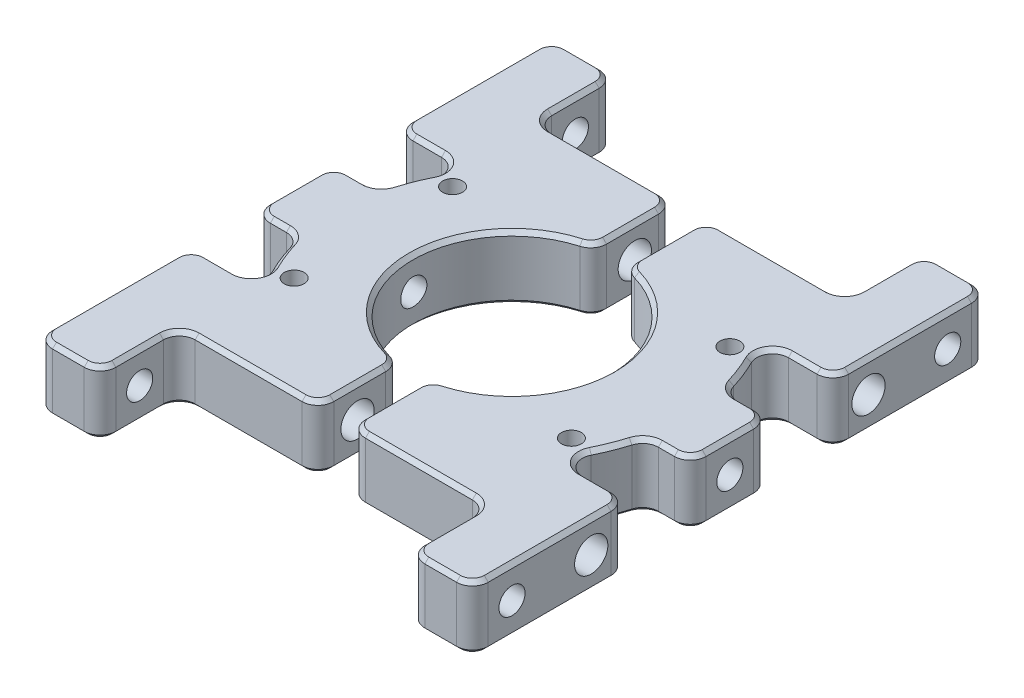
SolidWorks part; units mm, degrees
material "6061 合金"
ref_plane "前视基准面" through (0, 0, 0) normal (0, 0, 1) x (1, 0, 0)
ref_plane "上视基准面" through (0, 0, 0) normal (0, 1, 0) x (1, 0, 0)
ref_plane "右视基准面" through (0, 0, 0) normal (1, 0, 0) x (0, 0, -1)
sketch "草图1" plane through (0, 0, 0) normal (0, 1, 0) x (1, 0, 0)
  line L1 (-27.5, 22.5) -> (-2, 22.5)
  line L2 (-27.5, 22.5) -> (-27.5, -22.5)
  line L3 (-27.5, -22.5) -> (-2, -22.5)
  line L4 (27.5, 22.5) -> (27.5, -22.5)
  line L5 (-27.5, 22.5) -> (27.5, -22.5) construction
  line L6 (-27.5, -22.5) -> (27.5, 22.5) construction
  line L8 (-2, 22.5) -> (-2, 12.339)
  line L10 (2, 22.5) -> (2, 12.339)
  line L11 (2, 22.5) -> (27.5, 22.5)
  line L13 (2, -22.5) -> (27.5, -22.5)
  line L16 (2, -12.339) -> (2, -22.5)
  line L17 (-2, -12.339) -> (-2, -22.5)
  arc A0 (-2, 12.339) -> (-2, -12.339) centre (0, 0) ccw
  arc A1 (2, -12.339) -> (2, 12.339) centre (0, 0) ccw
  point P7 (0, 25)
  point P12 (0, 0)
  dimension "D1" = 25
  dimension "D2" = 55
  dimension "D3" = 45
  dimension "D4" = 4
  dimension "D5" = 2
  dimension "D6" = 4
  dimension "D7" = 2
extrude "凸台-拉伸1" add sketch "草图1" along normal mid plane 8 contours A0 L8 L1 L2 L3 | A0 L10 L3 L4 L1
sketch "草图7" plane through (0, 4, 0) normal (0, 1, 0) x (1, 0, 0)
  line L0 (27.5, 22.5) -> (27.5, -22.5) construction
  line L1 (19.5, 32.5) -> (27.5, 32.5)
  line L2 (19.5, 32.5) -> (19.5, -32.5)
  line L3 (19.5, -32.5) -> (27.5, -32.5)
  line L4 (27.5, 32.5) -> (27.5, -32.5)
  line L5 (-27.5, 32.5) -> (-19.5, 32.5)
  line L6 (-27.5, 32.5) -> (-27.5, -32.5)
  line L7 (-27.5, -32.5) -> (-19.5, -32.5)
  line L8 (-19.5, 32.5) -> (-19.5, -32.5)
  line L9 (-27.5, 22.5) -> (-27.5, -22.5) construction
  dimension "D1" = 8
  dimension "D2" = 65
  dimension "D3" = 32.5
extrude "凸台-拉伸2" add sketch "草图7" against normal up to surface (8 mm away) up to face at (12.25, -4, 0)
sketch "草图8" plane through (27.5, 0, 0) normal (1, 0, 0) x (0, 0, -1)
  line L0 (-17.5, 0) -> (17.5, 0) construction
  circle A0 centre (-17.5, 0) radius 2.1
  circle A1 centre (17.5, 0) radius 2.1
  circle A2 centre (0, 0) radius 1.5
  point P3 (0, 0)
  dimension "D2" = 4.2
  dimension "D3" = 3
  dimension "D1" = 35
extrude "切除-拉伸2" cut sketch "草图8" against normal through all
sketch "草图11" plane through (27.5, 0, 0) normal (1, 0, 0) x (0, 0, -1)
  line L0 (-27.5, 0) -> (27.5, 0) construction
  line L1 (32.5, -4) -> (32.5, 4) construction
  line L2 (-32.5, -4) -> (-32.5, 4) construction
  circle A0 centre (-27.5, 0) radius 1.5
  circle A1 centre (27.5, 0) radius 1.5
  dimension "D3" = 3
  dimension "D1" = 5
  dimension "D2" = 5
extrude "切除-拉伸3" cut sketch "草图11" against normal through all
sketch "草图12" plane through (0, 4, 0) normal (0, 1, 0) x (1, 0, 0)
  line L0 (-27.5, 0) -> (27.5, 0) construction
  line L1 (-27.5, 32.5) -> (-27.5, -32.5) construction
  line L2 (27.5, 32.5) -> (27.5, -32.5) construction
  line L3 (-27.5, -5) -> (27.5, -5)
  line L4 (-27.5, 5) -> (27.5, 5)
  line L5 (-27.5, -13) -> (27.5, -13)
  line L6 (-27.5, 13) -> (27.5, 13)
  line L7 (27.5, -13) -> (27.5, 13)
  line L8 (-27.5, 13) -> (-27.5, -13)
  line L10 (-17.5, 10) -> (17.5, 10) construction
  line L11 (-17.5, 10) -> (-17.5, -10) construction
  line L12 (-17.5, -10) -> (17.5, -10) construction
  line L13 (17.5, 10) -> (17.5, -10) construction
  line L14 (-17.5, 10) -> (17.5, -10) construction
  line L15 (-17.5, -10) -> (17.5, 10) construction
  circle A0 centre (0, 0) radius 22.5
  circle A1 centre (-17.5, -10) radius 1
  circle A2 centre (-17.5, 10) radius 1
  circle A3 centre (17.5, 10) radius 1
  circle A4 centre (17.5, -10) radius 1
  point P26 (19.8831, -10)
  line M6 (-27.5, 32.5) -> (-27.5, -32.5)
  dimension "D1" = 45
  dimension "D8" = 2
  dimension "D6" = 20
  dimension "D7" = 35
  dimension "D2" = 5
  dimension "D3" = 5
  dimension "D4" = 13
  dimension "D5" = 13
extrude "切除-拉伸5" cut sketch "草图12" against normal through all contours A0 L6 L4 M6 | A0 L3 L5 M6 | A0 L5 L7 L3 | A0 L4 L7 L6 | A2 | A1 | A4 | A3
fillet "圆角1" radius 2 18 edges at (27.5, 0, 5) (27.5, 0, -5) (21.9374, 0, -5) (18.3644, 0, -13) (27.5, 0, -13) (27.5, 0, -32.5) (19.5, 0, -32.5) (19.5, 0, -22.5) (2, 0, -22.5) (2, 0, -12.339) (2, 0, 12.339) (2, 0, 22.5) (19.5, 0, 22.5) (19.5, 0, 32.5) (27.5, 0, 13) (18.3644, 0, 13) (21.9374, 0, 5) (27.5, 0, 32.5)
fillet "圆角2" radius 2 18 edges at (-27.5, 0, 5) (-21.9374, 0, 5) (-18.3644, 0, 13) (-27.5, 0, 13) (-27.5, 0, 32.5) (-19.5, 0, 32.5) (-19.5, 0, 22.5) (-2, 0, 22.5) (-2, 0, 12.339) (-2, 0, -12.339) (-2, 0, -22.5) (-19.5, 0, -22.5) (-19.5, 0, -32.5) (-27.5, 0, -32.5) (-18.3644, 0, -13) (-21.9374, 0, -5) (-27.5, 0, -5) (-27.5, 0, -13)
hole_wizard "M4 螺纹孔3" positions "草图18" profile "草图19" tap size "M4" standard "ISO" end condition through all
sketch "草图18" plane through (-27.5, 0, 0) normal (-1, 0, 0) x (0, 0, 1)
  point P0 (-27.5, 0)
  point P3 (0, 0)
  point P6 (27.5, 0)
sketch "草图19" plane through (-27.5, 0, -27.5) normal (0, 1, 0) x (0, 0, 1)
  line L0 (0, 0) -> (0, 55)
  line L1 (0, 55) -> (1.65, 55)
  line L2 (1.65, 55) -> (1.65, 0)
  line L5 (1.65, 0) -> (0, 0)
  line L11 (0, -6.35) -> (0, 107.95) construction
  dimension "通孔螺纹孔钻头直径" = 3.3
  dimension "通孔螺纹孔钻头深度" = 55
cosmetic thread "孔螺蚊线6" parameters "D2"=4
cosmetic thread "孔螺蚊线7" parameters "D2"=4
cosmetic thread "孔螺蚊线8" parameters "D2"=4
hole_wizard "M3 螺纹孔1" positions "草图20" profile "草图21" tap size "M3" standard "ISO" end condition through all
sketch "草图20" plane through (0, 4, 0) normal (0, 1, 0) x (1, 0, 0)
  point P0 (17.5, 10)
  point P3 (17.5, -10)
  point P6 (-17.5, -10)
  point P9 (-17.5, 10)
sketch "草图21" plane through (17.5, 4, -10) normal (1, 0, 0) x (0, 0, 1)
  line L0 (0, 0) -> (0, 8)
  line L1 (0, 8) -> (1.25, 8)
  line L2 (1.25, 8) -> (1.25, 0)
  line L5 (1.25, 0) -> (0, 0)
  line L11 (0, -6.35) -> (0, 107.95) construction
  dimension "通孔螺纹孔钻头直径" = 2.5
  dimension "通孔螺纹孔钻头深度" = 8
cosmetic thread "孔螺蚊线9" parameters "D2"=3
cosmetic thread "孔螺蚊线10" parameters "D2"=3
cosmetic thread "孔螺蚊线11" parameters "D2"=3
cosmetic thread "孔螺蚊线12" parameters "D2"=3
chamfer "倒角1" distance 0.5 angle 45 72 edges at (-27.5, -4, 0) (-26.9142, -4, -4.4142) (-26.9142, -4, 4.4142) (-24.4894, -4, -5) (-24.4894, -4, 5) (-22.2835, -4, -5.3964) (-22.2835, -4, 5.3964) (-20.9142, -4, -8.2974) (-20.9142, -4, 8.2974) (-20.1894, -4, -12.0498) (-20.1894, -4, 12.0498) (-23.6959, -4, -13) (-23.6959, -4, 13) (-26.9142, -4, -13.5858) (-26.9142, -4, 13.5858) (-27.5, -4, -22.75) (-27.5, -4, 22.75) (-26.9142, -4, -31.9142) (-26.9142, -4, 31.9142) (-23.5, 4, -32.5) (-23.5, -4, -32.5) (-23.5, 4, 32.5) (-23.5, -4, 32.5) (-20.0858, -4, -31.9142) (-20.0858, -4, 31.9142) (-19.5, 4, -27.5) (-19.5, -4, -27.5) (-19.5, 4, 27.5) (-19.5, -4, 27.5) (-18.9142, -4, -23.0858) (-18.9142, -4, 23.0858) (-10.75, -4, -22.5) (-10.75, -4, 22.5) (-2.5858, -4, -21.9142) (-2.5858, -4, 21.9142) (-2, -4, -17.2187) (-2, -4, 17.2187) (-2.4026, -4, -12.7339) (-2.4026, -4, 12.7339) (-12.5, -4, 0) (-27.5, 4, 0) (-26.9142, 4, -4.4142) (-26.9142, 4, 4.4142) (-24.4894, 4, -5) (-24.4894, 4, 5) (-22.2835, 4, -5.3964) (-22.2835, 4, 5.3964) (-20.9142, 4, -8.2974) (-20.9142, 4, 8.2974) (-20.1894, 4, -12.0498) (-20.1894, 4, 12.0498) (-23.6959, 4, -13) (-23.6959, 4, 13) (-26.9142, 4, -13.5858) (-26.9142, 4, 13.5858) (-27.5, 4, -22.75) (-27.5, 4, 22.75) (-26.9142, 4, -31.9142) (-26.9142, 4, 31.9142) (-20.0858, 4, -31.9142) (-20.0858, 4, 31.9142) (-18.9142, 4, -23.0858) (-18.9142, 4, 23.0858) (-10.75, 4, -22.5) (-10.75, 4, 22.5) (-2.5858, 4, -21.9142) (-2.5858, 4, 21.9142) (-2, 4, -17.2187) (-2, 4, 17.2187) (-2.4026, 4, -12.7339) (-2.4026, 4, 12.7339) (-12.5, 4, 0)
chamfer "倒角2" distance 0.5 angle 45 72 edges at (27.5, -4, 0) (26.9142, -4, 4.4142) (26.9142, -4, -4.4142) (24.4894, -4, 5) (24.4894, -4, -5) (22.2835, -4, 5.3964) (22.2835, -4, -5.3964) (20.9142, -4, 8.2974) (20.9142, -4, -8.2974) (20.1894, -4, 12.0498) (20.1894, -4, -12.0498) (23.6959, -4, 13) (23.6959, -4, -13) (26.9142, -4, 13.5858) (26.9142, -4, -13.5858) (27.5, -4, 22.75) (27.5, -4, -22.75) (26.9142, -4, 31.9142) (26.9142, -4, -31.9142) (23.5, 4, 32.5) (23.5, -4, 32.5) (23.5, 4, -32.5) (23.5, -4, -32.5) (20.0858, -4, 31.9142) (20.0858, -4, -31.9142) (19.5, 4, 27.5) (19.5, -4, 27.5) (19.5, 4, -27.5) (19.5, -4, -27.5) (18.9142, -4, 23.0858) (18.9142, -4, -23.0858) (10.75, -4, 22.5) (10.75, -4, -22.5) (2.5858, -4, 21.9142) (2.5858, -4, -21.9142) (2, -4, 17.2187) (2, -4, -17.2187) (2.4026, -4, 12.7339) (2.4026, -4, -12.7339) (12.5, -4, 0) (27.5, 4, 0) (26.9142, 4, 4.4142) (26.9142, 4, -4.4142) (24.4894, 4, 5) (24.4894, 4, -5) (22.2835, 4, 5.3964) (22.2835, 4, -5.3964) (20.9142, 4, 8.2974) (20.9142, 4, -8.2974) (20.1894, 4, 12.0498) (20.1894, 4, -12.0498) (23.6959, 4, 13) (23.6959, 4, -13) (26.9142, 4, 13.5858) (26.9142, 4, -13.5858) (27.5, 4, 22.75) (27.5, 4, -22.75) (26.9142, 4, 31.9142) (26.9142, 4, -31.9142) (20.0858, 4, 31.9142) (20.0858, 4, -31.9142) (18.9142, 4, 23.0858) (18.9142, 4, -23.0858) (10.75, 4, 22.5) (10.75, 4, -22.5) (2.5858, 4, 21.9142) (2.5858, 4, -21.9142) (2, 4, 17.2187) (2, 4, -17.2187) (2.4026, 4, 12.7339) (2.4026, 4, -12.7339) (12.5, 4, 0)
